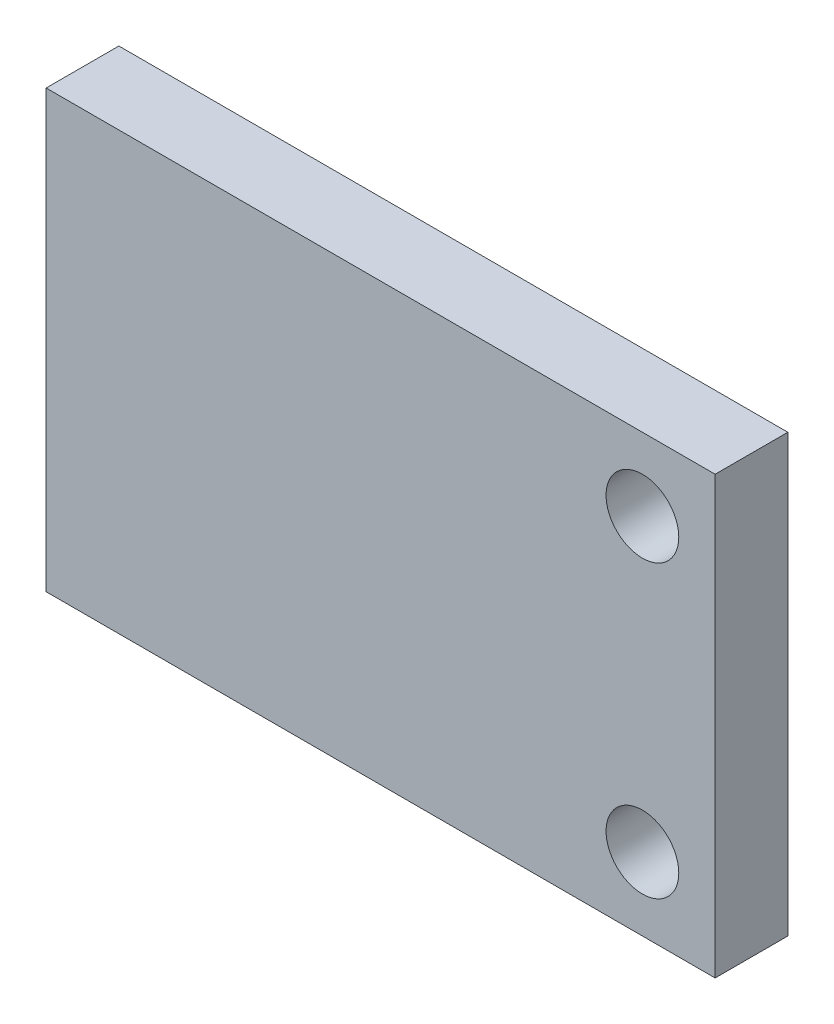
SolidWorks part; units mm, degrees
ref_plane "Płaszczyzna przednia" through (0, 0, 0) normal (0, 0, 1) x (1, 0, 0)
ref_plane "Płaszczyzna górna" through (0, 0, 0) normal (0, 1, 0) x (1, 0, 0)
ref_plane "Płaszczyzna prawa" through (0, 0, 0) normal (1, 0, 0) x (0, 0, -1)
sketch "Szkic1" plane through (0, 0, 0) normal (0, 0, 1) x (1, 0, 0)
  line L1 (-46, 30) -> (46, 30)
  line L2 (-46, 30) -> (-46, -30)
  line L3 (-46, -30) -> (46, -30)
  line L4 (46, 30) -> (46, -30)
  line L5 (-46, 30) -> (46, -30) construction
  line L6 (-46, -30) -> (46, 30) construction
  circle A0 centre (36, -20) radius 5
  circle A1 centre (36, 20) radius 5
  point P0 (0, 0)
  dimension "D3" = 10
  dimension "D6" = 10
  dimension "D1" = 60
  dimension "D2" = 92
  dimension "D4" = 10
  dimension "D5" = 10
  dimension "D7" = 10
  dimension "D8" = 10
extrude "Dodanie-wyciągnięcie1" add sketch "Szkic1" along normal blind 10
